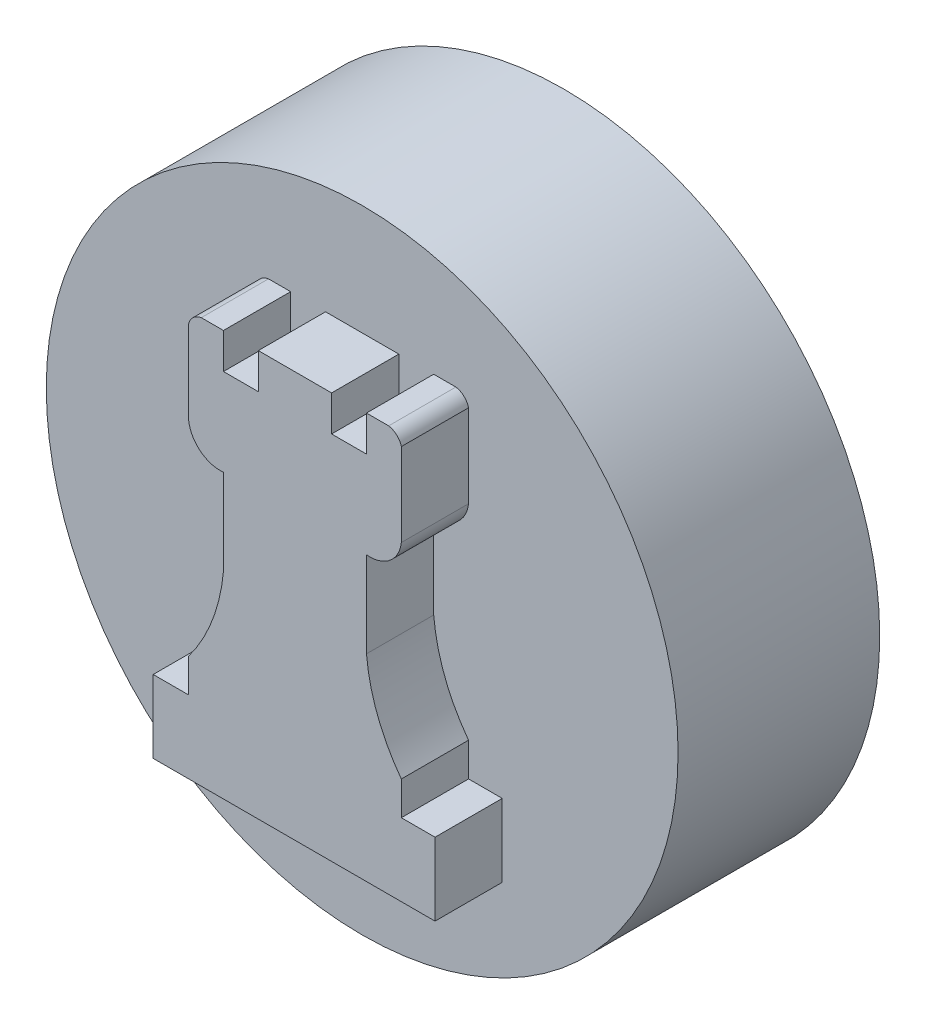
SolidWorks part; units mm, degrees
ref_plane "Front Plane" through (0, 0, 0) normal (0, 0, 1) x (1, 0, 0)
ref_plane "Top Plane" through (0, 0, 0) normal (0, 1, 0) x (1, 0, 0)
ref_plane "Right Plane" through (0, 0, 0) normal (1, 0, 0) x (0, 0, -1)
sketch "Sketch1" plane through (0, 0, 0) normal (0, 0, 1) x (1, 0, 0)
  circle A0 centre (0, 0) radius 8.763
  circle A1 centre (0, 0) radius 11.938
  dimension "D1" = 17.526
  dimension "D2" = 23.876
extrude "Boss-Extrude1" add sketch "Sketch1" along normal blind 5.08
sketch "Sketch2" plane through (0, 0, 5.08) normal (0, 0, 1) x (1, 0, 0)
  circle A0 centre (0, 0) radius 11.938
extrude "Boss-Extrude2" add sketch "Sketch2" along normal blind 2.54
sketch "Sketch3" plane through (0, 0, 7.62) normal (0, 0, 1) x (1, 0, 0)
  line L0 (76.4074, 247.7537) -> (417.7408, 247.7537) construction
  line L1 (31.9897, 119.1312) -> (202.6564, 119.1312) construction
  line L30 (33.3333, 100.0554) -> (166.6667, 100.0554) construction
  line L31 (76.5513, 248.4132) -> (417.8847, 248.4132) construction
  line L50 (33.4547, 119.6194) -> (204.1214, 119.6194) construction
  line L63 (146.8553, 495.6562) -> (829.522, 495.6562) construction
  line L64 (32.8546, 118.5983) -> (203.5213, 118.5983) construction
  line L88 (0, 4.0767) -> (0, 10.7108) construction
  line L102 (75.7654, 247.0659) -> (417.0987, 247.0659) construction
  line L118 (1.3849, 7.7649) -> (-1.3849, 7.7649)
  line L119 (-5.3572, -7.568) -> (5.2932, -7.568)
  line L120 (-5.3572, -7.568) -> (-5.3572, -4.8207)
  line L121 (-5.3572, -4.8207) -> (-4.0197, -4.8207)
  line L122 (5.2932, -7.568) -> (5.2932, -4.8207)
  line L123 (-1.3849, 7.7649) -> (-1.3849, 6.4209)
  line L124 (-1.3849, 6.4209) -> (-2.7027, 6.4209)
  line L125 (-2.7027, 6.4209) -> (-2.7027, 7.7649)
  line L126 (-2.7027, 7.7649) -> (-3.5407, 7.7649)
  line L127 (-4.0197, 7.3258) -> (-4.0197, 4.1852)
  line L128 (-2.7027, -0.1157) -> (-2.7027, 3.1273)
  line L129 (-4.0197, -4.8207) -> (-4.0197, -3.5529)
  line L130 (1.3849, 7.7649) -> (1.3849, 6.4209)
  line L131 (1.3849, 6.4209) -> (2.7027, 6.4209)
  line L132 (2.7027, 6.4209) -> (2.7027, 7.7649)
  line L133 (2.7027, 7.7649) -> (3.5407, 7.7649)
  line L134 (4.0197, 7.3258) -> (4.0197, 4.1852)
  line L135 (2.7027, -0.1157) -> (2.7027, 3.1273)
  line L136 (4.0197, -4.8207) -> (4.0197, -3.5529)
  line L137 (4.0197, -4.8207) -> (5.2932, -4.8207)
  arc A34 (-4.0197, -3.5529) -> (-2.7027, -0.1157) centre (-9.4036, 0.4809) ccw
  arc A35 (-2.7027, 3.1273) -> (-4.0197, 4.1852) centre (-2.8323, 4.3148) cw
  arc A36 (-3.5407, 7.7649) -> (-4.0197, 7.3258) centre (-3.4438, 7.1784) ccw
  arc A37 (3.5407, 7.7649) -> (4.0197, 7.3258) centre (3.4438, 7.1784) cw
  arc A38 (2.7027, 3.1273) -> (4.0197, 4.1852) centre (2.8323, 4.3148) ccw
  arc A39 (4.0197, -3.5529) -> (2.7027, -0.1157) centre (9.4036, 0.4809) cw
  point P39 (0, 7.7649)
extrude "Boss-Extrude8" add sketch "Sketch3" along normal blind 2.54 contours A35 L127 A36 L126 L125 L124 L123 L118 L130 L131 L132 L133 A37 L134 A38 L135 A39 L136 L137 L122 L119 L120 L121 L129 A34 L128
